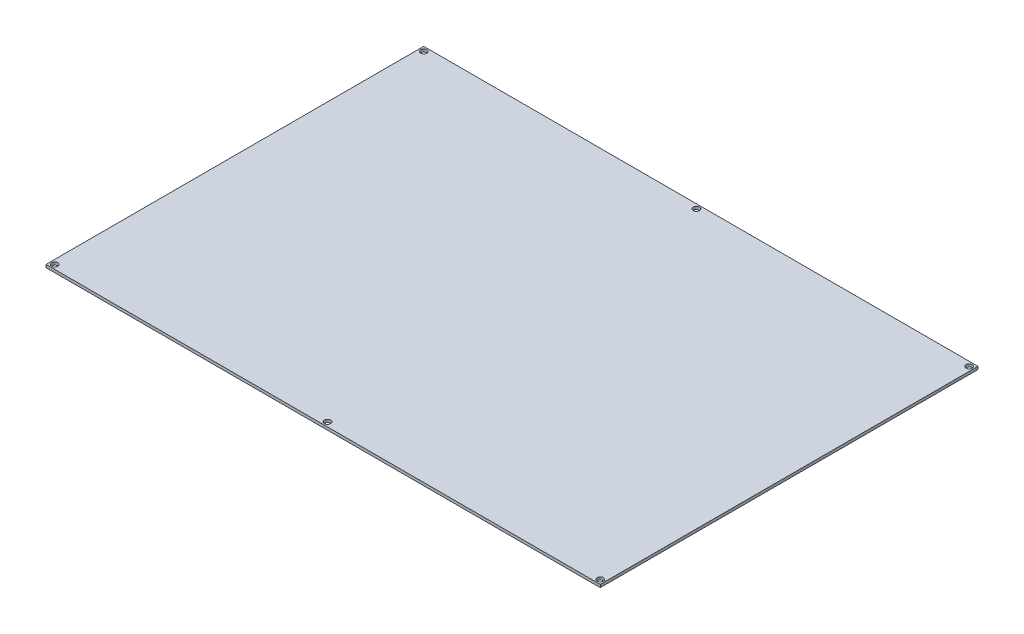
SolidWorks part; units mm, degrees
ref_plane "Front Plane" through (0, 0, 0) normal (0, 0, 1) x (1, 0, 0)
ref_plane "Top Plane" through (0, 0, 0) normal (0, 1, 0) x (1, 0, 0)
ref_plane "Right Plane" through (0, 0, 0) normal (1, 0, 0) x (0, 0, -1)
sketch "Sketch1" plane through (0, 0, 0) normal (0, 1, 0) x (1, 0, 0)
  line L1 (0, 0) -> (314, 0)
  line L2 (0, 0) -> (0, 214)
  line L3 (0, 214) -> (314, 214)
  line L4 (314, 0) -> (314, 214)
  dimension "D1" = 314
  dimension "D2" = 214
extrude "Boss-Extrude1" add sketch "Sketch1" along normal blind 1.6
sketch "Sketch2" plane through (0, 1.6, 0) normal (0, 1, 0) x (1, 0, 0)
  line L0 (0, 214) -> (0, 0) construction
  line L1 (0, 0) -> (314, 0) construction
  circle A0 centre (2.5, 2.5) radius 1.75
  circle A1 centre (311.5, 2.5) radius 1.75
  circle A2 centre (2.5, 211.5) radius 1.75
  circle A4 centre (311.5, 211.5) radius 1.75
  circle A5 centre (157, 2.5) radius 1.75
  circle A6 centre (157, 211.5) radius 1.75
  dimension "D1" = 3.5
  dimension "D2" = 3.5
  dimension "D5" = 3.5
  dimension "D6" = 3.5
  dimension "D9" = 3.5
  dimension "D11" = 3.5
  dimension "D3" = 309
  dimension "D4" = 2.5
  dimension "D7" = 209
  dimension "D8" = 2.5
  dimension "D10" = 154.5
extrude "Cut-Extrude1" cut sketch "Sketch2" against normal through all
